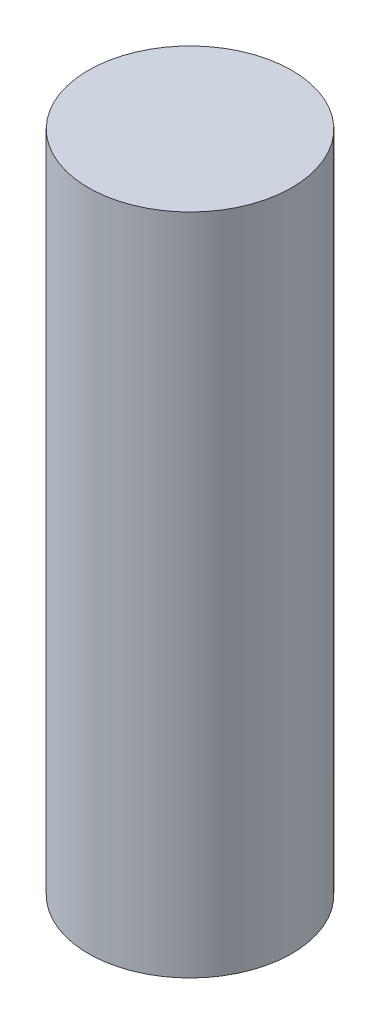
SolidWorks part; units mm, degrees
material "6061-T6 (SS)"
ref_plane "Front Plane" through (0, 0, 0) normal (0, 0, 1) x (1, 0, 0)
ref_plane "Top Plane" through (0, 0, 0) normal (0, 1, 0) x (1, 0, 0)
ref_plane "Right Plane" through (0, 0, 0) normal (1, 0, 0) x (0, 0, -1)
sketch "Sketch1" plane through (0, 0, 0) normal (0, 1, 0) x (1, 0, 0)
  circle A0 centre (0, 0) radius 2.921
  dimension "D1" = 5.842
extrude "Boss-Extrude1" add sketch "Sketch1" along normal blind 19.05
